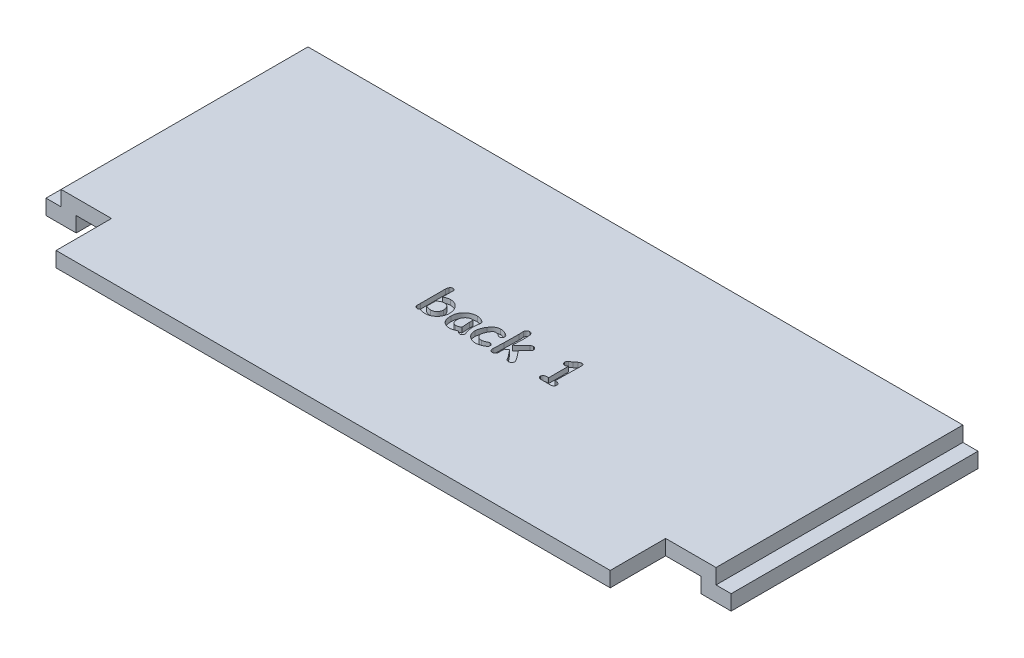
SolidWorks part; units mm, degrees
material "ABS"
ref_plane "前基準面" through (0, 0, 0) normal (0, 0, 1) x (1, 0, 0)
ref_plane "上基準面" through (0, 0, 0) normal (0, 1, 0) x (1, 0, 0)
ref_plane "右基準面" through (0, 0, 0) normal (1, 0, 0) x (0, 0, -1)
sketch "草圖1" plane through (0, 0, 0) normal (0, 0, 1) x (1, 0, 0)
  line L1 (-102.0286, 1.9929) -> (7.9714, 1.9929)
  line L2 (-102.0286, 1.9929) -> (-102.0286, -1.0071)
  line L3 (-102.0286, -1.0071) -> (7.9714, -1.0071)
  line L4 (7.9714, 1.9929) -> (7.9714, -1.0071)
  dimension "D1" = 3
  dimension "D2" = 110
extrude "填料-伸長1" add sketch "草圖1" along normal blind 11
sketch "草圖2" plane through (0, 0, 0) normal (0, 0, -1) x (-1, 0, 0)
  line L0 (102.0286, -1.0071) -> (-7.9714, -1.0071) construction
  line L1 (115.0286, -1.0071) -> (-20.9714, -1.0071)
  line L2 (115.0286, -1.0071) -> (115.0286, 1.9929)
  line L3 (115.0286, 1.9929) -> (-20.9714, 1.9929)
  line L4 (-20.9714, -1.0071) -> (-20.9714, 1.9929)
  line L5 (-7.9714, 1.9929) -> (102.0286, 1.9929) construction
  line L6 (-7.9714, -1.0071) -> (-7.9714, 1.9929) construction
  line L7 (102.0286, 1.9929) -> (102.0286, -1.0071) construction
  dimension "D1" = 13
  dimension "D2" = 13
extrude "填料-伸長2" add sketch "草圖2" along normal blind 14
sketch "草圖3" plane through (0, 0, -14) normal (0, 0, -1) x (-1, 0, 0)
  line L0 (115.0286, -1.0071) -> (115.0286, 1.9929) construction
  line L1 (-20.9714, 1.9929) -> (115.0286, 1.9929)
  line L2 (-20.9714, 1.9929) -> (-20.9714, -4.0071)
  line L3 (-20.9714, -4.0071) -> (115.0286, -4.0071)
  line L4 (115.0286, 1.9929) -> (115.0286, -4.0071)
  line L5 (-20.9714, -1.0071) -> (115.0286, -1.0071) construction
  dimension "D1" = 3
extrude "填料-伸長3" add sketch "草圖3" along normal blind 3
sketch "草圖4" plane through (0, 0, -17) normal (0, 0, -1) x (-1, 0, 0)
  line L0 (-20.9714, 1.9929) -> (-20.9714, -4.0071) construction
  line L1 (115.0286, -4.0071) -> (-20.9714, -4.0071)
  line L2 (115.0286, -4.0071) -> (115.0286, -1.0071)
  line L3 (115.0286, -1.0071) -> (-20.9714, -1.0071)
  line L4 (-20.9714, -4.0071) -> (-20.9714, -1.0071)
  line L5 (115.0286, 1.9929) -> (-20.9714, 1.9929) construction
  line L6 (112.0286, -1.0071) -> (-17.9714, -1.0071)
  line L7 (112.0286, -1.0071) -> (112.0286, 1.9929)
  line L8 (112.0286, 1.9929) -> (-17.9714, 1.9929)
  line L9 (-17.9714, -1.0071) -> (-17.9714, 1.9929)
  line L10 (115.0286, -4.0071) -> (115.0286, 1.9929) construction
  line M2 (-20.9714, 1.9929) -> (-20.9714, -4.0071)
  line M3 (-20.9714, -4.0071) -> (115.0286, -4.0071)
  line M4 (115.0286, -4.0071) -> (115.0286, 1.9929)
  line M5 (115.0286, 1.9929) -> (-20.9714, 1.9929)
  dimension "D1" = 3
  dimension "D2" = 3
  dimension "D3" = 3
extrude "填料-伸長4" add sketch "草圖4" along normal blind 32 contours L3 M4 M2 M3 | L9 L3 L7 M5
sketch "草圖10" plane through (0, -1.0071, 0) normal (0, -1, 0) x (1, 0, 0)
  line L0 (20.9714, 0) -> (7.9714, 0) construction
  line L1 (20.9714, -14) -> (14.9714, -14)
  line L2 (20.9714, -14) -> (20.9714, 0)
  line L3 (20.9714, 0) -> (14.9714, 0)
  line L4 (14.9714, -14) -> (14.9714, 0)
  line L5 (-102.0286, 0) -> (-115.0286, 0) construction
  line L6 (-115.0286, -14) -> (-109.0286, -14)
  line L7 (-115.0286, -14) -> (-115.0286, 0)
  line L8 (-115.0286, 0) -> (-109.0286, 0)
  line L9 (-109.0286, -14) -> (-109.0286, 0)
  dimension "D1" = 6
  dimension "D2" = 6
extrude "填料-伸長6" add sketch "草圖10" along normal up to surface (3 mm away) up to face at (-47.0286, -4.0071, -31.5)
sketch "草圖11" plane through (0, 1.9929, 0) normal (0, 1, 0) x (1, 0, 0)
  line L1 (20.9714, 0) -> (17.9714, 0)
  line L2 (20.9714, 0) -> (20.9714, 17)
  line L3 (20.9714, 17) -> (17.9714, 17)
  line L4 (17.9714, 0) -> (17.9714, 17)
  line L5 (-115.0286, 0) -> (-112.0286, 0)
  line L6 (-115.0286, 0) -> (-115.0286, 17)
  line L7 (-115.0286, 17) -> (-112.0286, 17)
  line L8 (-112.0286, 0) -> (-112.0286, 17)
extrude "除料-伸長2" cut sketch "草圖11" against normal blind 3
sketch "草圖12" plane through (0, -4.0071, 0) normal (0, -1, 0) x (1, 0, 0)
  line L0 (-109.0286, -14) -> (14.9714, -14)
  line L1 (-109.0286, -14) -> (-109.0286, -49.165)
  line L2 (14.9714, -14) -> (14.9714, -49.165)
  line L3 (-109.0286, -49.165) -> (14.9714, -49.165)
extrude "除料-伸長3" cut sketch "草圖12" against normal blind 3
sketch "草圖13" plane through (0, 1.9929, 0) normal (0, 1, 0) x (1, 0, 0)
  text T0 "back 1" font "Comic Sans MS" height in points 24
extrude "除料-伸長4" cut sketch "草圖13" against normal blind 1
